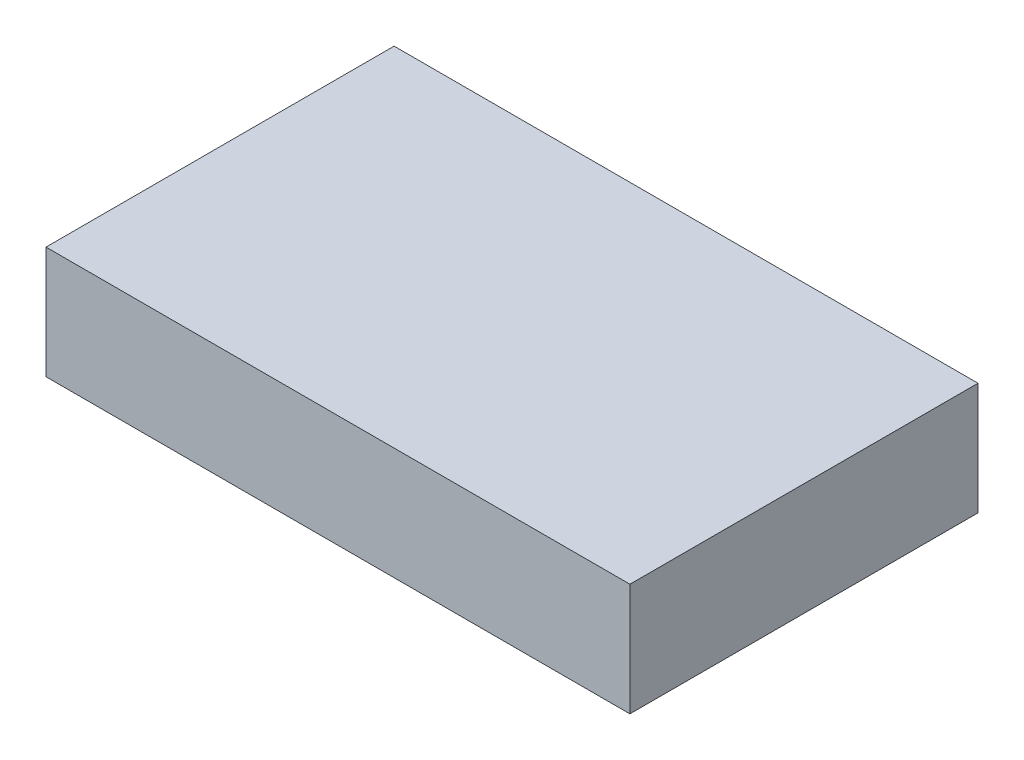
SolidWorks part; units mm, degrees
ref_plane "Front Plane" through (0, 0, 0) normal (0, 0, 1) x (1, 0, 0)
ref_plane "Top Plane" through (0, 0, 0) normal (0, 1, 0) x (1, 0, 0)
ref_plane "Right Plane" through (0, 0, 0) normal (1, 0, 0) x (0, 0, -1)
sketch "Sketch1" plane through (0, 0, 0) normal (0, 1, 0) x (1, 0, 0)
  line L1 (-82.55, -49.2125) -> (82.55, -49.2125)
  line L2 (-82.55, -49.2125) -> (-82.55, 49.2125)
  line L3 (-82.55, 49.2125) -> (82.55, 49.2125)
  line L4 (82.55, -49.2125) -> (82.55, 49.2125)
  line L5 (-82.55, -49.2125) -> (82.55, 49.2125) construction
  line L6 (-82.55, 49.2125) -> (82.55, -49.2125) construction
  point P0 (0, 0)
  dimension "D1" = 165.1
  dimension "D2" = 98.425
extrude "Boss-Extrude1" add sketch "Sketch1" along normal blind 31.75
